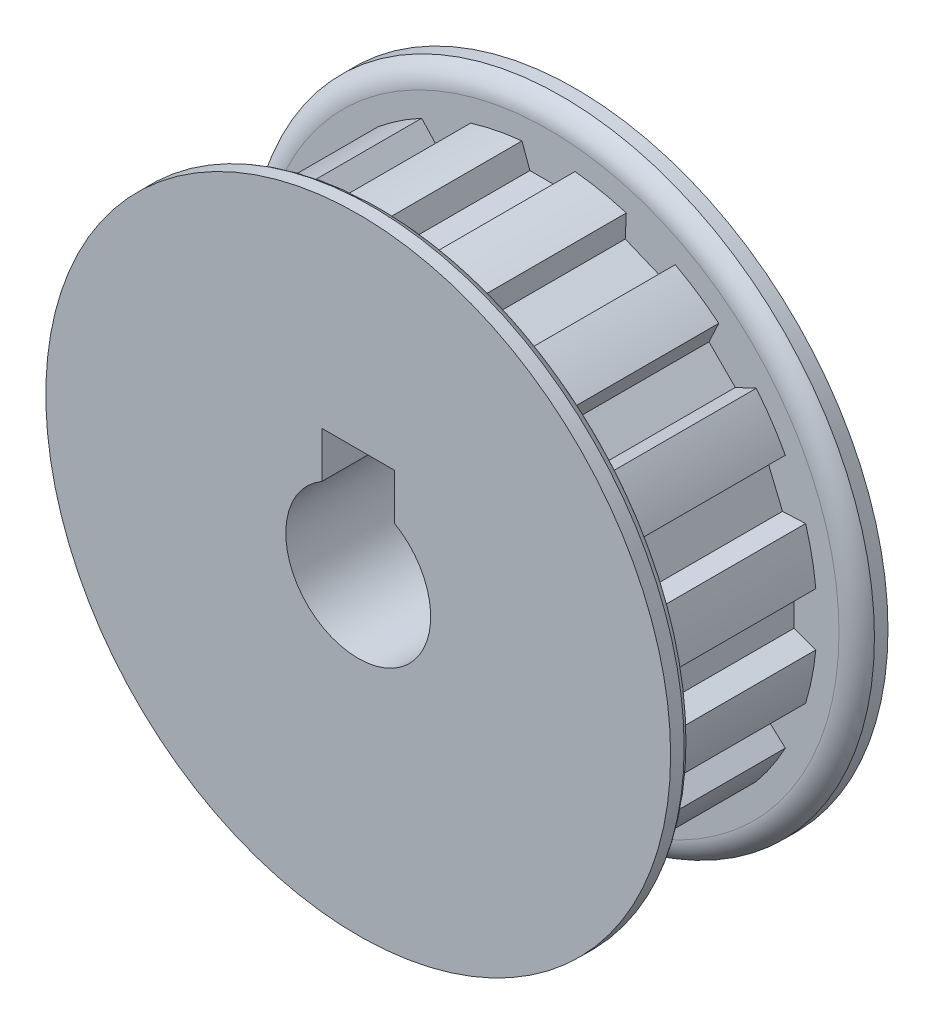
SolidWorks part; units mm, degrees
ref_plane "Front Plane" through (0, 0, 0) normal (0, 0, 1) x (1, 0, 0)
ref_plane "Top Plane" through (0, 0, 0) normal (0, 1, 0) x (1, 0, 0)
ref_plane "Right Plane" through (0, 0, 0) normal (1, 0, 0) x (0, 0, -1)
sketch "Sketch1" plane through (0, 0, 0) normal (0, 0, 1) x (1, 0, 0)
  line L0 (-2.3241, 23.4315) -> (-1.6307, 21.5265)
  line L1 (-1.6307, 21.5265) -> (1.6307, 21.5265)
  line L2 (1.6307, 21.5265) -> (2.3241, 23.4315)
  line L3 (-2.3241, 23.4315) -> (2.3241, 23.4315)
  line L4 (0, 0) -> (0, 21.5265) construction
  line L5 (0, 21.5265) -> (0, 25.0825) construction
  circle A0 centre (0, 0) radius 24.257 construction
  circle A1 centre (0, 0) radius 27.3812 construction
  circle A2 centre (0, 0) radius 23.5465 construction
  point P6 (0, 23.4315)
  point P11 (0, 24.257)
  point P13 (0, 27.3812)
  point P14 (0, 23.5465)
  dimension "D1" = 1.651
  dimension "PD" = 48.514
  dimension "D2" = 0.8255
  dimension "OD" = 54.7624
  dimension "b" = 40
  dimension "bt" = 4.6482
  dimension "ht" = 1.905
  dimension "hs" = 3.556
sketch "Sketch2" plane through (0, 0, 0) normal (1, 0, 0) x (0, 0, -1)
  line L0 (-17.4625, 6.35) -> (17.4625, 6.35)
  line L1 (-17.4625, 6.35) -> (-17.4625, 18.2626)
  line L2 (-17.4625, 18.2626) -> (-1.5875, 18.2626)
  line L3 (-1.5875, 18.2626) -> (-1.5875, 27.3812)
  line L4 (-1.5875, 27.3812) -> (0.7874, 27.3812) construction
  line L5 (0.7874, 27.3812) -> (0.7874, 23.5465) construction
  line L6 (0.7874, 23.5465) -> (15.0876, 23.5465)
  line L7 (15.0876, 23.5465) -> (15.0876, 27.3812) construction
  line L8 (15.0876, 27.3812) -> (17.4625, 27.3812) construction
  line L9 (17.4625, 27.3812) -> (17.4625, 6.35)
  line L10 (-17.4625, 0) -> (17.4625, 0) construction
  line L13 (-1.5875, 27.3812) -> (-0.4001, 27.3812)
  line L14 (0.7874, 25.4638) -> (0.7874, 23.5465)
  line L15 (15.0876, 23.5465) -> (15.0876, 25.4638)
  line L16 (16.2751, 27.3812) -> (17.4625, 27.3812)
  arc A0 (0.7874, 25.4638) -> (-0.4001, 27.3812) centre (-1.3543, 25.4638) ccw
  arc A1 (15.0876, 25.4638) -> (16.2751, 27.3812) centre (17.2293, 25.4638) cw
  point P12 (0.7874, 25.4638)
  point P14 (-0.4001, 27.3812)
  point P20 (15.0876, 25.4638)
  point P21 (16.2751, 27.3812)
  point P25 (15.0876, 0)
  point P26 (0.7874, 0)
  dimension "Bore" = 12.7
  dimension "Hub Dia" = 36.5252
  dimension "Outside Width" = 19.05
  dimension "Inside Width" = 14.3002
revolve "Revolve1" add sketch "Sketch2" angle 360 mid plane about L10
sketch "Sketch3" plane through (0, 0, 0) normal (0, 0, 1) x (1, 0, 0)
  line L0 (-1.6307, 21.5265) -> (1.6307, 21.5265) construction
  line L1 (1.6307, 21.5265) -> (2.3241, 23.4315) construction
  line L2 (-2.3241, 23.4315) -> (-1.6307, 21.5265) construction
  line L3 (-1.6307, 21.5265) -> (1.6307, 21.5265)
  line L4 (1.6307, 21.5265) -> (2.3241, 23.4315)
  line L5 (-2.3241, 23.4315) -> (-1.6307, 21.5265)
  circle A0 centre (0, 0) radius 23.5465 construction
  arc A1 (2.3241, 23.4315) -> (-2.3241, 23.4315) centre (0, 0) ccw
extrude "Cut-Extrude1" cut sketch "Sketch3" against normal up to vertex (15.0876 mm away) from vertex at -0.7874 starting at point (0, 23.5465, -0.7874)
pattern_circular "CirPattern1" count 16 over 360 about axis through (0, 0, 0) along (0, 0, 1) of "Cut-Extrude1"
sketch "Sketch4" plane through (0, 0, 0) normal (1, 0, 0) x (0, -1, 0)
  line L0 (0, -1.5875) -> (0, -17.4625) construction
  line L1 (-18.2626, -1.5875) -> (18.2626, -1.5875) construction
  line L2 (-18.2626, -17.4625) -> (18.2626, -17.4625) construction
  circle A0 centre (0, -9.525) radius 3.175
  dimension "D1" = 6.35
extrude "Cut-Extrude2" cut sketch "Sketch4" along normal through all
ref_plane "Plane1" through (0, 0, 9.525) normal (0, 0, 1) x (1, 0, 0)
sketch "Sketch5" plane through (0, 0, 0) normal (0, 0, 1) x (1, 0, 0)
  circle A0 centre (0, 0) radius 30.0044
extrude "Cut-Extrude3" cut sketch "Sketch5" along normal blind 20.32 from surface at 1.5875 starting at face at (18.2626, 0, 1.5875)
sketch "Sketch6" plane through (0, 0, 0) normal (0, 0, 1) x (1, 0, 0)
  line L0 (0, 0) -> (0, 6.35) construction
  line L1 (-3.175, 9.525) -> (3.175, 9.525)
  line L2 (-3.175, 9.525) -> (-3.175, 3.175)
  line L3 (-3.175, 3.175) -> (3.175, 3.175)
  line L4 (3.175, 9.525) -> (3.175, 3.175)
  line L5 (-3.175, 9.525) -> (3.175, 3.175) construction
  line L6 (-3.175, 3.175) -> (3.175, 9.525) construction
  point P0 (0, 6.35)
  point P8 (0, 6.35)
  dimension "D1" = 6.35
  dimension "D2" = 6.35
  dimension "D3" = 6.35
extrude "Cut-Extrude4" cut sketch "Sketch6" against normal blind 20.32 and the other way blind 20.32
equation "\"D1@Sketch4\" = \"Bore@Sketch2\"/2"
